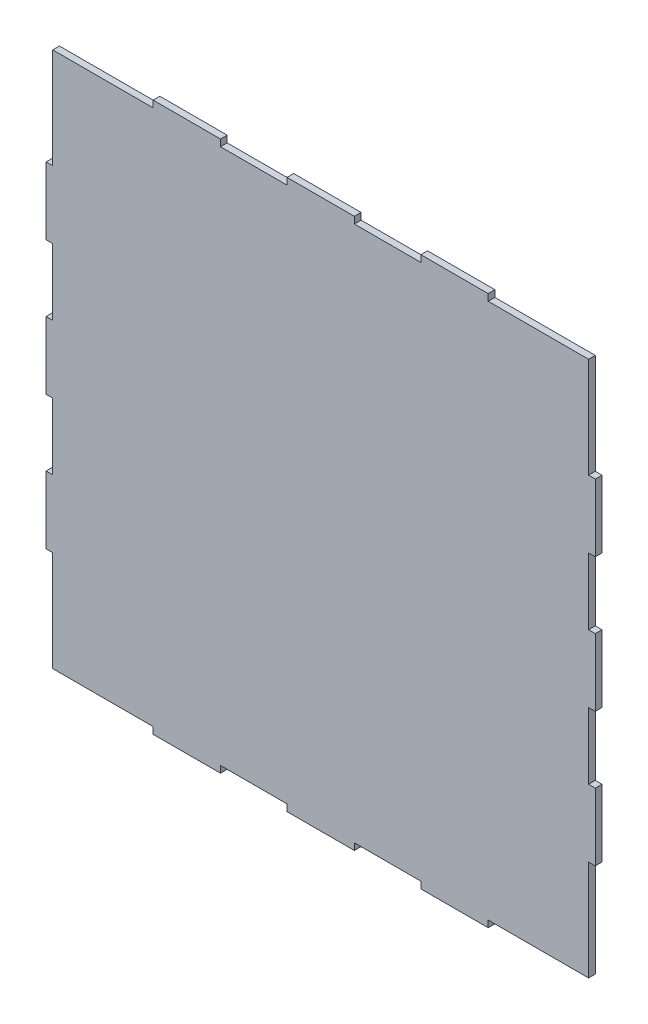
SolidWorks part; units mm, degrees
ref_plane "Ebene vorne" through (0, 0, 0) normal (0, 0, 1) x (1, 0, 0)
ref_plane "Ebene oben" through (0, 0, 0) normal (0, 1, 0) x (1, 0, 0)
ref_plane "Ebene rechts" through (0, 0, 0) normal (1, 0, 0) x (0, 0, -1)
sketch "Skizze1" plane through (0, 0, 0) normal (0, 0, 1) x (1, 0, 0)
  line L1 (0, 0) -> (410, 0)
  line L2 (0, 0) -> (0, 410)
  line L3 (0, 410) -> (410, 410)
  line L4 (410, 0) -> (410, 410)
  dimension "D1" = 410
  dimension "D2" = 410
extrude "Aufsatz-Linear austragen1" add sketch "Skizze1" along normal blind 5 contours L2 L3 L4 L1
sketch "Skizze2" plane through (0, 0, 5) normal (0, 0, 1) x (1, 0, 0)
  line L0 (0, 410) -> (410, 410) construction
  line L1 (-92.7967, 379.65) -> (5, 379.65)
  line L2 (-92.7967, 379.65) -> (-92.7967, 330.05)
  line L3 (-92.7967, 330.05) -> (5, 330.05)
  line L4 (5, 379.65) -> (5, 330.05)
  dimension "D1" = 49.6
  dimension "D2" = 5
  dimension "D3" = 79.95
extrude "Schnitt-Linear austragen1" cut sketch "Skizze2" against normal blind 5
pattern_linear "Lineares Muster1" count 4 spacing 99.9 along (0, -1, 0) of "Schnitt-Linear austragen1"
ref_plane "Ebene1" through (205, 0, 0) normal (1, 0, 0) x (0, 0, -1)
mirror "Spiegeln1" about plane through (205, 0, 0) normal (1, 0, 0) of "Schnitt-Linear austragen1", "Lineares Muster1"
sketch "Skizze3" plane through (0, 0, 5) normal (0, 0, 1) x (1, 0, 0)
  line L0 (0, 410) -> (410, 410) construction
  line L1 (30.35, 446.7791) -> (79.95, 446.7791)
  line L2 (30.35, 446.7791) -> (30.35, 405)
  line L3 (30.35, 405) -> (79.95, 405)
  line L4 (79.95, 446.7791) -> (79.95, 405)
  dimension "D1" = 49.6
  dimension "D2" = 5
  dimension "D3" = 79.95
extrude "Schnitt-Linear austragen2" cut sketch "Skizze3" against normal blind 5
pattern_linear "Lineares Muster2" count 4 spacing 99.9 along (1, 0, 0) of "Schnitt-Linear austragen2"
ref_plane "Ebene2" through (0, 205, 0) normal (0, 1, 0) x (1, 0, 0)
mirror "Spiegeln2" about plane through (0, 205, 0) normal (0, 1, 0) of "Schnitt-Linear austragen2", "Lineares Muster2"
sketch "Skizze4" plane through (0, 0, 5) normal (0, 0, 1) x (1, 0, 0)
  line L0 (5, 379.65) -> (5, 405)
  line L1 (30.35, 405) -> (5, 405)
  line L7 (5, 379.65) -> (-47.8629, 379.65)
  line L10 (-47.8629, 379.65) -> (-47.8629, 405)
  line L12 (-47.8629, 405) -> (-47.8629, 431.5498)
  line L13 (-47.8629, 431.5498) -> (5, 431.5498)
  line L17 (5, 431.5498) -> (30.35, 431.5498)
  line L18 (30.35, 405) -> (30.35, 431.5498)
extrude "Schnitt-Linear austragen3" cut sketch "Skizze4" against normal blind 5
mirror "Spiegeln3" about plane through (205, 0, 0) normal (1, 0, 0) of "Schnitt-Linear austragen3"
mirror "Spiegeln4" about plane through (0, 205, 0) normal (0, 1, 0) of "Schnitt-Linear austragen3", "Spiegeln3"
sketch "Skizze5" plane through (0, 410, 0) normal (0, 1, 0) x (1, 0, 0)
  line L0 (130.25, -5) -> (130.25, 0) construction
  line L1 (130.25, 0) -> (79.95, 0) construction
  line L2 (79.95, 0) -> (79.95, -5) construction
  line L3 (79.95, -5) -> (130.25, -5) construction
  line L4 (230.15, -5) -> (230.15, 0) construction
  line L5 (230.15, 0) -> (179.85, 0) construction
  line L6 (179.85, 0) -> (179.85, -5) construction
  line L7 (179.85, -5) -> (230.15, -5) construction
  line L8 (330.05, -5) -> (330.05, 0) construction
  line L9 (330.05, 0) -> (279.75, 0) construction
  line L10 (279.75, 0) -> (279.75, -5) construction
  line L11 (279.75, -5) -> (330.05, -5) construction
  line L12 (405, 0) -> (405, -5) construction
  line L13 (5, 0) -> (5, -5) construction
  line L14 (130.25, -5) -> (130.25, 0)
  line L15 (130.25, 0) -> (79.95, 0)
  line L16 (79.95, 0) -> (79.95, -5)
  line L17 (79.95, -5) -> (130.25, -5)
  line L18 (230.15, -5) -> (230.15, 0)
  line L19 (230.15, 0) -> (179.85, 0)
  line L20 (179.85, 0) -> (179.85, -5)
  line L21 (179.85, -5) -> (230.15, -5)
  line L22 (330.05, -5) -> (330.05, 0)
  line L23 (330.05, 0) -> (279.75, 0)
  line L24 (279.75, 0) -> (279.75, -5)
  line L25 (279.75, -5) -> (330.05, -5)
  line L26 (405, 0) -> (405, -5)
  line L27 (5, 0) -> (5, -5)
